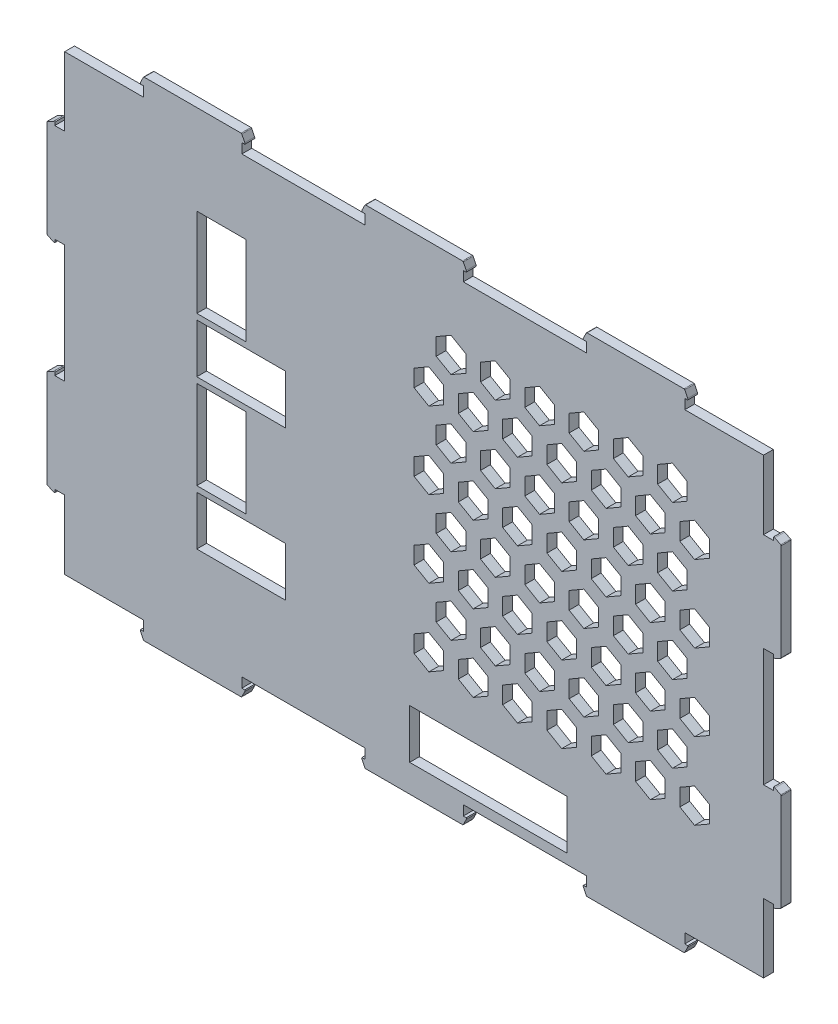
SolidWorks part; units mm, degrees
ref_plane "Front Plane" through (0, 0, 0) normal (0, 0, 1) x (1, 0, 0)
ref_plane "Top Plane" through (0, 0, 0) normal (0, 1, 0) x (1, 0, 0)
ref_plane "Right Plane" through (0, 0, 0) normal (1, 0, 0) x (0, 0, -1)
sketch "Sketch1" plane through (0, 0, 0) normal (0, 0, 1) x (1, 0, 0)
  line L0 (0, 0) -> (142, 0) construction
  line L1 (142, -46) -> (142, 46) construction
  line L2 (142, 46) -> (0, 46) construction
  line L3 (0, 46) -> (0, -46) construction
  line L8 (0, -46) -> (142, -46) construction
  line L30 (71, 46) -> (71, -46) construction
  line L31 (0, 32) -> (0, 46)
  line L32 (0, 46) -> (16, 46)
  line L35 (36, 46) -> (61, 46)
  line L37 (81, 46) -> (106, 46)
  line L39 (126, 46) -> (142, 46)
  line L40 (142, 46) -> (142, 32)
  line L43 (142, -46) -> (126, -46)
  line L46 (106, -46) -> (81, -46)
  line L48 (61, -46) -> (36, -46)
  line L50 (16, -46) -> (0, -46)
  line L51 (0, -46) -> (0, -32)
  line L52 (0, -12) -> (0, 12)
  line L54 (142, 12) -> (142, -12)
  line L56 (142, -32) -> (142, -46)
  line B0 (16, -46) -> (36, -46) construction
  line B1 (16.1618, -49.6) -> (35.8382, -49.6)
  line B2 (16, -46) -> (16, -48)
  line B3 (16, -49.5) -> (36, -49.5) construction
  line B4 (26, -49.5) -> (26, -46) construction
  line B5 (36, -46) -> (36, -48)
  line B6 (36.6, -48.3) -> (36, -49.5)
  line B7 (15.4, -48.3) -> (16, -49.5)
  line B8 (16, -48) -> (15.4, -48)
  line B9 (36, -48) -> (36.6, -48)
  arc B10 (16, -48) -> (15.4, -48.3) centre (15.7, -48.15) ccw construction
  arc B11 (16, -49.5) -> (16.1618, -49.6) centre (16.1618, -49.4191) ccw
  arc B12 (36, -49.5) -> (35.8382, -49.6) centre (35.8382, -49.4191) cw
  arc B13 (15.4, -48) -> (15.4, -48.3) centre (15.7, -48.15) ccw
  arc B14 (36.6, -48) -> (36.6, -48.3) centre (36.3, -48.15) cw
  line B15 (61, -46) -> (81, -46) construction
  line B16 (61.1618, -49.6) -> (80.8382, -49.6)
  line B17 (61, -46) -> (61, -48)
  line B18 (61, -49.5) -> (81, -49.5) construction
  line B19 (71, -49.5) -> (71, -46) construction
  line B20 (81, -46) -> (81, -48)
  line B21 (81.6, -48.3) -> (81, -49.5)
  line B22 (60.4, -48.3) -> (61, -49.5)
  line B23 (61, -48) -> (60.4, -48)
  line B24 (81, -48) -> (81.6, -48)
  arc B25 (61, -48) -> (60.4, -48.3) centre (60.7, -48.15) ccw construction
  arc B26 (61, -49.5) -> (61.1618, -49.6) centre (61.1618, -49.4191) ccw
  arc B27 (81, -49.5) -> (80.8382, -49.6) centre (80.8382, -49.4191) cw
  arc B28 (60.4, -48) -> (60.4, -48.3) centre (60.7, -48.15) ccw
  arc B29 (81.6, -48) -> (81.6, -48.3) centre (81.3, -48.15) cw
  line B30 (142, 12) -> (142, 32) construction
  line B31 (145.6, 12.1618) -> (145.6, 31.8382)
  line B32 (142, 12) -> (144, 12)
  line B33 (145.5, 12) -> (145.5, 32) construction
  line B34 (145.5, 22) -> (142, 22) construction
  line B35 (142, 32) -> (144, 32)
  line B36 (144.3, 32.6) -> (145.5, 32)
  line B37 (144.3, 11.4) -> (145.5, 12)
  line B38 (144, 12) -> (144, 11.4)
  line B39 (144, 32) -> (144, 32.6)
  arc B40 (144, 12) -> (144.3, 11.4) centre (144.15, 11.7) ccw construction
  arc B41 (145.5, 12) -> (145.6, 12.1618) centre (145.4191, 12.1618) ccw
  arc B42 (145.5, 32) -> (145.6, 31.8382) centre (145.4191, 31.8382) cw
  arc B43 (144, 11.4) -> (144.3, 11.4) centre (144.15, 11.7) ccw
  arc B44 (144, 32.6) -> (144.3, 32.6) centre (144.15, 32.3) cw
  line B45 (126, -46) -> (106, -46) construction
  line B46 (125.8382, -49.6) -> (106.1618, -49.6)
  line B47 (126, -46) -> (126, -48)
  line B48 (126, -49.5) -> (106, -49.5) construction
  line B49 (116, -49.5) -> (116, -46) construction
  line B50 (106, -46) -> (106, -48)
  line B51 (105.4, -48.3) -> (106, -49.5)
  line B52 (126.6, -48.3) -> (126, -49.5)
  line B53 (126, -48) -> (126.6, -48)
  line B54 (106, -48) -> (105.4, -48)
  arc B55 (126, -48) -> (126.6, -48.3) centre (126.3, -48.15) cw construction
  arc B56 (126, -49.5) -> (125.8382, -49.6) centre (125.8382, -49.4191) cw
  arc B57 (106, -49.5) -> (106.1618, -49.6) centre (106.1618, -49.4191) ccw
  arc B58 (126.6, -48) -> (126.6, -48.3) centre (126.3, -48.15) cw
  arc B59 (105.4, -48) -> (105.4, -48.3) centre (105.7, -48.15) ccw
  line B60 (16, 46) -> (36, 46) construction
  line B61 (16.1618, 49.6) -> (35.8382, 49.6)
  line B62 (16, 46) -> (16, 48)
  line B63 (16, 49.5) -> (36, 49.5) construction
  line B64 (26, 49.5) -> (26, 46) construction
  line B65 (36, 46) -> (36, 48)
  line B66 (36.6, 48.3) -> (36, 49.5)
  line B67 (15.4, 48.3) -> (16, 49.5)
  line B68 (16, 48) -> (15.4, 48)
  line B69 (36, 48) -> (36.6, 48)
  arc B70 (16, 48) -> (15.4, 48.3) centre (15.7, 48.15) cw construction
  arc B71 (16, 49.5) -> (16.1618, 49.6) centre (16.1618, 49.4191) cw
  arc B72 (36, 49.5) -> (35.8382, 49.6) centre (35.8382, 49.4191) ccw
  arc B73 (15.4, 48) -> (15.4, 48.3) centre (15.7, 48.15) cw
  arc B74 (36.6, 48) -> (36.6, 48.3) centre (36.3, 48.15) ccw
  line B75 (61, 46) -> (81, 46) construction
  line B76 (61.1618, 49.6) -> (80.8382, 49.6)
  line B77 (61, 46) -> (61, 48)
  line B78 (61, 49.5) -> (81, 49.5) construction
  line B79 (71, 49.5) -> (71, 46) construction
  line B80 (81, 46) -> (81, 48)
  line B81 (81.6, 48.3) -> (81, 49.5)
  line B82 (60.4, 48.3) -> (61, 49.5)
  line B83 (61, 48) -> (60.4, 48)
  line B84 (81, 48) -> (81.6, 48)
  arc B85 (61, 48) -> (60.4, 48.3) centre (60.7, 48.15) cw construction
  arc B86 (61, 49.5) -> (61.1618, 49.6) centre (61.1618, 49.4191) cw
  arc B87 (81, 49.5) -> (80.8382, 49.6) centre (80.8382, 49.4191) ccw
  arc B88 (60.4, 48) -> (60.4, 48.3) centre (60.7, 48.15) cw
  arc B89 (81.6, 48) -> (81.6, 48.3) centre (81.3, 48.15) ccw
  line B90 (126, 46) -> (106, 46) construction
  line B91 (125.8382, 49.6) -> (106.1618, 49.6)
  line B92 (126, 46) -> (126, 48)
  line B93 (126, 49.5) -> (106, 49.5) construction
  line B94 (116, 49.5) -> (116, 46) construction
  line B95 (106, 46) -> (106, 48)
  line B96 (105.4, 48.3) -> (106, 49.5)
  line B97 (126.6, 48.3) -> (126, 49.5)
  line B98 (126, 48) -> (126.6, 48)
  line B99 (106, 48) -> (105.4, 48)
  arc B100 (126, 48) -> (126.6, 48.3) centre (126.3, 48.15) ccw construction
  arc B101 (126, 49.5) -> (125.8382, 49.6) centre (125.8382, 49.4191) ccw
  arc B102 (106, 49.5) -> (106.1618, 49.6) centre (106.1618, 49.4191) cw
  arc B103 (126.6, 48) -> (126.6, 48.3) centre (126.3, 48.15) ccw
  arc B104 (105.4, 48) -> (105.4, 48.3) centre (105.7, 48.15) cw
  line B105 (0, 12) -> (0, 32) construction
  line B106 (-3.6, 12.1618) -> (-3.6, 31.8382)
  line B107 (0, 12) -> (-2, 12)
  line B108 (-3.5, 12) -> (-3.5, 32) construction
  line B109 (-3.5, 22) -> (0, 22) construction
  line B110 (0, 32) -> (-2, 32)
  line B111 (-2.3, 32.6) -> (-3.5, 32)
  line B112 (-2.3, 11.4) -> (-3.5, 12)
  line B113 (-2, 12) -> (-2, 11.4)
  line B114 (-2, 32) -> (-2, 32.6)
  arc B115 (-2, 12) -> (-2.3, 11.4) centre (-2.15, 11.7) cw construction
  arc B116 (-3.5, 12) -> (-3.6, 12.1618) centre (-3.4191, 12.1618) cw
  arc B117 (-3.5, 32) -> (-3.6, 31.8382) centre (-3.4191, 31.8382) ccw
  arc B118 (-2, 11.4) -> (-2.3, 11.4) centre (-2.15, 11.7) cw
  arc B119 (-2, 32.6) -> (-2.3, 32.6) centre (-2.15, 32.3) ccw
  line B120 (26.8458, 12.2196) -> (44.8458, 12.2196)
  line B121 (26.8458, 12.2196) -> (26.8458, 2.2196)
  line B122 (26.8458, 2.2196) -> (44.8458, 2.2196)
  line B123 (44.8458, 12.2196) -> (44.8458, 2.2196)
  line B124 (26.8458, -18.0919) -> (44.8458, -18.0919)
  line B125 (26.8458, -18.0919) -> (26.8458, -28.0919)
  line B126 (26.8458, -28.0919) -> (44.8458, -28.0919)
  line B127 (44.8458, -18.0919) -> (44.8458, -28.0919)
  line B128 (36.8458, 1.0639) -> (36.8458, -16.9361)
  line B129 (36.8458, 1.0639) -> (26.8458, 1.0639)
  line B130 (26.8458, 1.0639) -> (26.8458, -16.9361)
  line B131 (36.8458, -16.9361) -> (26.8458, -16.9361)
  line B132 (36.8458, 31.3754) -> (36.8458, 13.3754)
  line B133 (36.8458, 31.3754) -> (26.8458, 31.3754)
  line B134 (26.8458, 31.3754) -> (26.8458, 13.3754)
  line B135 (36.8458, 13.3754) -> (26.8458, 13.3754)
  line B136 (26.8458, 13.3754) -> (26.8458, 12.2196) construction
  line B137 (26.8458, 2.2196) -> (26.8458, 1.0639) construction
  line B138 (26.8458, -16.9361) -> (26.8458, -18.0919) construction
  line B139 (70.1, -34) -> (102.1, -34)
  line B140 (70.1, -34) -> (70.1, -44)
  line B141 (70.1, -44) -> (102.1, -44)
  line B142 (102.1, -34) -> (102.1, -44)
  line B143 (0, 46) -> (142, 46) construction
  line B144 (142, 46) -> (142, -46) construction
  line B145 (142, -46) -> (0, -46) construction
  line B146 (0, -46) -> (0, 46) construction
  line B147 (142, -12) -> (142, -32) construction
  line B148 (145.6, -12.1618) -> (145.6, -31.8382)
  line B149 (142, -12) -> (144, -12)
  line B150 (145.5, -12) -> (145.5, -32) construction
  line B151 (145.5, -22) -> (142, -22) construction
  line B152 (142, -32) -> (144, -32)
  line B153 (144.3, -32.6) -> (145.5, -32)
  line B154 (144.3, -11.4) -> (145.5, -12)
  line B155 (144, -12) -> (144, -11.4)
  line B156 (144, -32) -> (144, -32.6)
  arc B157 (144, -12) -> (144.3, -11.4) centre (144.15, -11.7) cw construction
  arc B158 (145.5, -12) -> (145.6, -12.1618) centre (145.4191, -12.1618) cw
  arc B159 (145.5, -32) -> (145.6, -31.8382) centre (145.4191, -31.8382) ccw
  arc B160 (144, -11.4) -> (144.3, -11.4) centre (144.15, -11.7) cw
  arc B161 (144, -32.6) -> (144.3, -32.6) centre (144.15, -32.3) ccw
  line B162 (0, -12) -> (0, -32) construction
  line B163 (-3.6, -12.1618) -> (-3.6, -31.8382)
  line B164 (0, -12) -> (-2, -12)
  line B165 (-3.5, -12) -> (-3.5, -32) construction
  line B166 (-3.5, -22) -> (0, -22) construction
  line B167 (0, -32) -> (-2, -32)
  line B168 (-2.3, -32.6) -> (-3.5, -32)
  line B169 (-2.3, -11.4) -> (-3.5, -12)
  line B170 (-2, -12) -> (-2, -11.4)
  line B171 (-2, -32) -> (-2, -32.6)
  arc B172 (-2, -12) -> (-2.3, -11.4) centre (-2.15, -11.7) ccw construction
  arc B173 (-3.5, -12) -> (-3.6, -12.1618) centre (-3.4191, -12.1618) ccw
  arc B174 (-3.5, -32) -> (-3.6, -31.8382) centre (-3.4191, -31.8382) cw
  arc B175 (-2, -11.4) -> (-2.3, -11.4) centre (-2.15, -11.7) ccw
  arc B176 (-2, -32.6) -> (-2.3, -32.6) centre (-2.15, -32.3) cw
  dimension "D2" = 22
  dimension "D3" = 45
  dimension "D1" = 142
sketch_block_instance "insert_bloquant_20mm-2mm-1"
sketch_block "insert_bloquant_20mm-2mm" parameters "D1"=2, "D2"=1.5, "D3"=1.2, "D4"=20, "D5"=0.1, "D6"=0.6
sketch_block_instance "insert_bloquant_20mm-2mm-2"
sketch_block_instance "insert_bloquant_20mm-2mm-4"
sketch_block_instance "insert_bloquant_20mm-2mm-6"
sketch_block_instance "insert_bloquant_20mm-2mm-7"
sketch_block_instance "insert_bloquant_20mm-2mm-8"
sketch_block_instance "insert_bloquant_20mm-2mm-9"
sketch_block_instance "insert_bloquant_20mm-2mm-13"
sketch_block_instance "Bloc1-1"
sketch_block "Bloc1" parameters "D1"=10, "D2"=32
sketch_block_instance "Block1-1"
sketch_block "Block1" parameters "D1"=18, "D2"=10
sketch_block_instance "Block1-2"
sketch_block_instance "Block1-3"
sketch_block_instance "Block1-4"
sketch_block_instance "insert_bloquant_20mm-2mm-14"
sketch_block_instance "insert_bloquant_20mm-2mm-15"
extrude "Boss-Extrude1" add sketch "Sketch1" along normal blind 2
sketch "Esquisse1" plane through (0, 0, 2) normal (0, 0, 1) x (1, 0, 0)
  line L5 (71, 49.6) -> (71, -49.6) construction
  line L6 (61.1618, 49.6) -> (80.8382, 49.6) construction
  line L7 (61.1618, -49.6) -> (80.8382, -49.6) construction
  line B0 (131, 10.236) -> (128, 11.968)
  line B1 (128, 11.968) -> (125, 10.236)
  line B2 (120.5, 14.5661) -> (123.5, 12.834)
  line B3 (126.5, 14.5661) -> (126.5, 18.0302)
  line B4 (126.5, 18.0302) -> (123.5, 19.7622)
  line B5 (123.5, 19.7622) -> (120.5, 18.0302)
  line B6 (122, 6.7719) -> (122, 10.236)
  line B7 (122, 10.236) -> (119, 11.968)
  line B8 (119, 11.968) -> (116, 10.236)
  line B9 (111.5, 14.5661) -> (114.5, 12.834)
  line B10 (117.5, 14.5661) -> (117.5, 18.0302)
  line B11 (117.5, 18.0302) -> (114.5, 19.7622)
  line B12 (114.5, 19.7622) -> (111.5, 18.0302)
  line B13 (107, 6.7719) -> (110, 5.0398)
  line B14 (113, 6.7719) -> (113, 10.236)
  line B15 (113, 10.236) -> (110, 11.968)
  line B16 (110, 11.968) -> (107, 10.236)
  line B17 (102.5, 14.5661) -> (105.5, 12.834)
  line B18 (108.5, 14.5661) -> (108.5, 18.0302)
  line B19 (108.5, 18.0302) -> (105.5, 19.7622)
  line B20 (105.5, 19.7622) -> (102.5, 18.0302)
  line B21 (98, 6.7719) -> (101, 5.0398)
  line B22 (95, 6.7719) -> (95, 10.236)
  line B23 (128, 5.0398) -> (131, 6.7719)
  line B24 (104, 6.7719) -> (104, 10.236)
  line B25 (104, 10.236) -> (101, 11.968)
  line B26 (101, 11.968) -> (98, 10.236)
  line B27 (95, 10.236) -> (92, 11.968)
  line B28 (92, 11.968) -> (89, 10.236)
  line B29 (84.5, 14.5661) -> (87.5, 12.834)
  line B30 (90.5, 14.5661) -> (90.5, 18.0302)
  line B31 (90.5, 18.0302) -> (87.5, 19.7622)
  line B32 (87.5, 19.7622) -> (84.5, 18.0302)
  line B33 (80, 6.7719) -> (83, 5.0398)
  line B34 (86, 6.7719) -> (86, 10.236)
  line B35 (86, 10.236) -> (83, 11.968)
  line B36 (83, 11.968) -> (80, 10.236)
  line B37 (75.5, 14.5661) -> (78.5, 12.834)
  line B38 (81.5, 14.5661) -> (81.5, 18.0302)
  line B39 (81.5, 18.0302) -> (78.5, 19.7622)
  line B40 (78.5, 19.7622) -> (75.5, 18.0302)
  line B41 (71, 6.7719) -> (74, 5.0398)
  line B42 (77, 6.7719) -> (77, 10.236)
  line B43 (77, 10.236) -> (74, 11.968)
  line B44 (74, 11.968) -> (71, 10.236)
  line B45 (99.5, 18.0302) -> (96.5, 19.7622)
  line B46 (96.5, 19.7622) -> (93.5, 18.0302)
  line B47 (125, 6.7719) -> (128, 5.0398)
  line B48 (131, 6.7719) -> (131, 10.236)
  line B49 (125, 10.236) -> (125, 6.7719)
  line B50 (123.5, 12.834) -> (126.5, 14.5661)
  line B51 (120.5, 18.0302) -> (120.5, 14.5661)
  line B52 (80, 10.236) -> (80, 6.7719)
  line B53 (83, 5.0398) -> (86, 6.7719)
  line B54 (98, 10.236) -> (98, 6.7719)
  line B55 (101, 5.0398) -> (104, 6.7719)
  line B56 (116, 10.236) -> (116, 6.7719)
  line B57 (116, 6.7719) -> (119, 5.0398)
  line B58 (119, 5.0398) -> (122, 6.7719)
  line B59 (111.5, 18.0302) -> (111.5, 14.5661)
  line B60 (114.5, 12.834) -> (117.5, 14.5661)
  line B61 (74, 5.0398) -> (77, 6.7719)
  line B62 (71, 10.236) -> (71, 6.7719)
  line B63 (78.5, 12.834) -> (81.5, 14.5661)
  line B64 (75.5, 18.0302) -> (75.5, 14.5661)
  line B65 (92, 5.0398) -> (95, 6.7719)
  line B66 (89, 6.7719) -> (92, 5.0398)
  line B67 (89, 10.236) -> (89, 6.7719)
  line B68 (87.5, 12.834) -> (90.5, 14.5661)
  line B69 (84.5, 18.0302) -> (84.5, 14.5661)
  line B70 (96.5, 12.834) -> (99.5, 14.5661)
  line B71 (93.5, 14.5661) -> (96.5, 12.834)
  line B72 (93.5, 18.0302) -> (93.5, 14.5661)
  line B73 (99.5, 14.5661) -> (99.5, 18.0302)
  line B74 (110, 5.0398) -> (113, 6.7719)
  line B75 (107, 10.236) -> (107, 6.7719)
  line B76 (105.5, 12.834) -> (108.5, 14.5661)
  line B77 (102.5, 18.0302) -> (102.5, 14.5661)
  line B78 (131, 25.8244) -> (128, 27.5565)
  line B79 (128, 27.5565) -> (125, 25.8244)
  line B80 (120.5, 30.1546) -> (123.5, 28.4225)
  line B81 (126.5, 30.1546) -> (126.5, 33.6187)
  line B82 (126.5, 33.6187) -> (123.5, 35.3507)
  line B83 (123.5, 35.3507) -> (120.5, 33.6187)
  line B84 (122, 22.3603) -> (122, 25.8244)
  line B85 (122, 25.8244) -> (119, 27.5565)
  line B86 (119, 27.5565) -> (116, 25.8244)
  line B87 (111.5, 30.1546) -> (114.5, 28.4225)
  line B88 (117.5, 30.1546) -> (117.5, 33.6187)
  line B89 (117.5, 33.6187) -> (114.5, 35.3507)
  line B90 (114.5, 35.3507) -> (111.5, 33.6187)
  line B91 (107, 22.3603) -> (110, 20.6283)
  line B92 (113, 22.3603) -> (113, 25.8244)
  line B93 (113, 25.8244) -> (110, 27.5565)
  line B94 (110, 27.5565) -> (107, 25.8244)
  line B95 (102.5, 30.1546) -> (105.5, 28.4225)
  line B96 (108.5, 30.1546) -> (108.5, 33.6187)
  line B97 (108.5, 33.6187) -> (105.5, 35.3507)
  line B98 (105.5, 35.3507) -> (102.5, 33.6187)
  line B99 (98, 22.3603) -> (101, 20.6283)
  line B100 (95, 22.3603) -> (95, 25.8244)
  line B101 (128, 20.6283) -> (131, 22.3603)
  line B102 (104, 22.3603) -> (104, 25.8244)
  line B103 (104, 25.8244) -> (101, 27.5565)
  line B104 (101, 27.5565) -> (98, 25.8244)
  line B105 (95, 25.8244) -> (92, 27.5565)
  line B106 (92, 27.5565) -> (89, 25.8244)
  line B107 (84.5, 30.1546) -> (87.5, 28.4225)
  line B108 (90.5, 30.1546) -> (90.5, 33.6187)
  line B109 (90.5, 33.6187) -> (87.5, 35.3507)
  line B110 (87.5, 35.3507) -> (84.5, 33.6187)
  line B111 (80, 22.3603) -> (83, 20.6283)
  line B112 (86, 22.3603) -> (86, 25.8244)
  line B113 (86, 25.8244) -> (83, 27.5565)
  line B114 (83, 27.5565) -> (80, 25.8244)
  line B115 (75.5, 30.1546) -> (78.5, 28.4225)
  line B116 (81.5, 30.1546) -> (81.5, 33.6187)
  line B117 (81.5, 33.6187) -> (78.5, 35.3507)
  line B118 (78.5, 35.3507) -> (75.5, 33.6187)
  line B119 (71, 22.3603) -> (74, 20.6283)
  line B120 (77, 22.3603) -> (77, 25.8244)
  line B121 (77, 25.8244) -> (74, 27.5565)
  line B122 (74, 27.5565) -> (71, 25.8244)
  line B123 (99.5, 33.6187) -> (96.5, 35.3507)
  line B124 (96.5, 35.3507) -> (93.5, 33.6187)
  line B125 (125, 22.3603) -> (128, 20.6283)
  line B126 (131, 22.3603) -> (131, 25.8244)
  line B127 (125, 25.8244) -> (125, 22.3603)
  line B128 (123.5, 28.4225) -> (126.5, 30.1546)
  line B129 (120.5, 33.6187) -> (120.5, 30.1546)
  line B130 (80, 25.8244) -> (80, 22.3603)
  line B131 (83, 20.6283) -> (86, 22.3603)
  line B132 (98, 25.8244) -> (98, 22.3603)
  line B133 (101, 20.6283) -> (104, 22.3603)
  line B134 (116, 25.8244) -> (116, 22.3603)
  line B135 (116, 22.3603) -> (119, 20.6283)
  line B136 (119, 20.6283) -> (122, 22.3603)
  line B137 (111.5, 33.6187) -> (111.5, 30.1546)
  line B138 (114.5, 28.4225) -> (117.5, 30.1546)
  line B139 (74, 20.6283) -> (77, 22.3603)
  line B140 (71, 25.8244) -> (71, 22.3603)
  line B141 (78.5, 28.4225) -> (81.5, 30.1546)
  line B142 (75.5, 33.6187) -> (75.5, 30.1546)
  line B143 (92, 20.6283) -> (95, 22.3603)
  line B144 (89, 22.3603) -> (92, 20.6283)
  line B145 (89, 25.8244) -> (89, 22.3603)
  line B146 (87.5, 28.4225) -> (90.5, 30.1546)
  line B147 (84.5, 33.6187) -> (84.5, 30.1546)
  line B148 (96.5, 28.4225) -> (99.5, 30.1546)
  line B149 (93.5, 30.1546) -> (96.5, 28.4225)
  line B150 (93.5, 33.6187) -> (93.5, 30.1546)
  line B151 (99.5, 30.1546) -> (99.5, 33.6187)
  line B152 (110, 20.6283) -> (113, 22.3603)
  line B153 (107, 25.8244) -> (107, 22.3603)
  line B154 (105.5, 28.4225) -> (108.5, 30.1546)
  line B155 (102.5, 33.6187) -> (102.5, 30.1546)
  line B156 (131, -20.9409) -> (128, -19.2089)
  line B157 (128, -19.2089) -> (125, -20.9409)
  line B158 (120.5, -16.6108) -> (123.5, -18.3429)
  line B159 (126.5, -16.6108) -> (126.5, -13.1467)
  line B160 (126.5, -13.1467) -> (123.5, -11.4147)
  line B161 (123.5, -11.4147) -> (120.5, -13.1467)
  line B162 (122, -24.4051) -> (122, -20.9409)
  line B163 (122, -20.9409) -> (119, -19.2089)
  line B164 (119, -19.2089) -> (116, -20.9409)
  line B165 (111.5, -16.6108) -> (114.5, -18.3429)
  line B166 (117.5, -16.6108) -> (117.5, -13.1467)
  line B167 (117.5, -13.1467) -> (114.5, -11.4147)
  line B168 (114.5, -11.4147) -> (111.5, -13.1467)
  line B169 (107, -24.4051) -> (110, -26.1371)
  line B170 (113, -24.4051) -> (113, -20.9409)
  line B171 (113, -20.9409) -> (110, -19.2089)
  line B172 (110, -19.2089) -> (107, -20.9409)
  line B173 (102.5, -16.6108) -> (105.5, -18.3429)
  line B174 (108.5, -16.6108) -> (108.5, -13.1467)
  line B175 (108.5, -13.1467) -> (105.5, -11.4147)
  line B176 (105.5, -11.4147) -> (102.5, -13.1467)
  line B177 (98, -24.4051) -> (101, -26.1371)
  line B178 (95, -24.4051) -> (95, -20.9409)
  line B179 (128, -26.1371) -> (131, -24.4051)
  line B180 (104, -24.4051) -> (104, -20.9409)
  line B181 (104, -20.9409) -> (101, -19.2089)
  line B182 (101, -19.2089) -> (98, -20.9409)
  line B183 (95, -20.9409) -> (92, -19.2089)
  line B184 (92, -19.2089) -> (89, -20.9409)
  line B185 (84.5, -16.6108) -> (87.5, -18.3429)
  line B186 (90.5, -16.6108) -> (90.5, -13.1467)
  line B187 (90.5, -13.1467) -> (87.5, -11.4147)
  line B188 (87.5, -11.4147) -> (84.5, -13.1467)
  line B189 (80, -24.4051) -> (83, -26.1371)
  line B190 (86, -24.4051) -> (86, -20.9409)
  line B191 (86, -20.9409) -> (83, -19.2089)
  line B192 (83, -19.2089) -> (80, -20.9409)
  line B193 (75.5, -16.6108) -> (78.5, -18.3429)
  line B194 (81.5, -16.6108) -> (81.5, -13.1467)
  line B195 (81.5, -13.1467) -> (78.5, -11.4147)
  line B196 (78.5, -11.4147) -> (75.5, -13.1467)
  line B197 (71, -24.4051) -> (74, -26.1371)
  line B198 (77, -24.4051) -> (77, -20.9409)
  line B199 (77, -20.9409) -> (74, -19.2089)
  line B200 (74, -19.2089) -> (71, -20.9409)
  line B201 (99.5, -13.1467) -> (96.5, -11.4147)
  line B202 (96.5, -11.4147) -> (93.5, -13.1467)
  line B203 (125, -24.4051) -> (128, -26.1371)
  line B204 (131, -24.4051) -> (131, -20.9409)
  line B205 (125, -20.9409) -> (125, -24.4051)
  line B206 (123.5, -18.3429) -> (126.5, -16.6108)
  line B207 (120.5, -13.1467) -> (120.5, -16.6108)
  line B208 (80, -20.9409) -> (80, -24.4051)
  line B209 (83, -26.1371) -> (86, -24.4051)
  line B210 (98, -20.9409) -> (98, -24.4051)
  line B211 (101, -26.1371) -> (104, -24.4051)
  line B212 (128, -22.673) -> (71, -22.673) construction
  line B213 (116, -20.9409) -> (116, -24.4051)
  line B214 (116, -24.4051) -> (119, -26.1371)
  line B215 (119, -26.1371) -> (122, -24.4051)
  line B216 (111.5, -13.1467) -> (111.5, -16.6108)
  line B217 (114.5, -18.3429) -> (117.5, -16.6108)
  line B218 (74, -26.1371) -> (77, -24.4051)
  line B219 (71, -20.9409) -> (71, -24.4051)
  line B220 (78.5, -18.3429) -> (81.5, -16.6108)
  line B221 (75.5, -13.1467) -> (75.5, -16.6108)
  line B222 (92, -26.1371) -> (95, -24.4051)
  line B223 (89, -24.4051) -> (92, -26.1371)
  line B224 (89, -20.9409) -> (89, -24.4051)
  line B225 (87.5, -18.3429) -> (90.5, -16.6108)
  line B226 (84.5, -13.1467) -> (84.5, -16.6108)
  line B227 (96.5, -18.3429) -> (99.5, -16.6108)
  line B228 (93.5, -16.6108) -> (96.5, -18.3429)
  line B229 (93.5, -13.1467) -> (93.5, -16.6108)
  line B230 (99.5, -16.6108) -> (99.5, -13.1467)
  line B231 (110, -26.1371) -> (113, -24.4051)
  line B232 (107, -20.9409) -> (107, -24.4051)
  line B233 (105.5, -18.3429) -> (108.5, -16.6108)
  line B234 (102.5, -13.1467) -> (102.5, -16.6108)
  line B235 (131, -5.3525) -> (128, -3.6204)
  line B236 (128, -3.6204) -> (125, -5.3525)
  line B237 (120.5, -1.0224) -> (123.5, -2.7544)
  line B238 (126.5, -1.0224) -> (126.5, 2.4417)
  line B239 (126.5, 2.4417) -> (123.5, 4.1738)
  line B240 (123.5, 4.1738) -> (120.5, 2.4417)
  line B241 (122, -8.8166) -> (122, -5.3525)
  line B242 (122, -5.3525) -> (119, -3.6204)
  line B243 (119, -3.6204) -> (116, -5.3525)
  line B244 (111.5, -1.0224) -> (114.5, -2.7544)
  line B245 (117.5, -1.0224) -> (117.5, 2.4417)
  line B246 (117.5, 2.4417) -> (114.5, 4.1738)
  line B247 (114.5, 4.1738) -> (111.5, 2.4417)
  line B248 (107, -8.8166) -> (110, -10.5486)
  line B249 (113, -8.8166) -> (113, -5.3525)
  line B250 (113, -5.3525) -> (110, -3.6204)
  line B251 (110, -3.6204) -> (107, -5.3525)
  line B252 (102.5, -1.0224) -> (105.5, -2.7544)
  line B253 (108.5, -1.0224) -> (108.5, 2.4417)
  line B254 (108.5, 2.4417) -> (105.5, 4.1738)
  line B255 (105.5, 4.1738) -> (102.5, 2.4417)
  line B256 (98, -8.8166) -> (101, -10.5486)
  line B257 (95, -8.8166) -> (95, -5.3525)
  line B258 (128, -10.5486) -> (131, -8.8166)
  line B259 (104, -8.8166) -> (104, -5.3525)
  line B260 (104, -5.3525) -> (101, -3.6204)
  line B261 (101, -3.6204) -> (98, -5.3525)
  line B262 (95, -5.3525) -> (92, -3.6204)
  line B263 (92, -3.6204) -> (89, -5.3525)
  line B264 (84.5, -1.0224) -> (87.5, -2.7544)
  line B265 (90.5, -1.0224) -> (90.5, 2.4417)
  line B266 (90.5, 2.4417) -> (87.5, 4.1738)
  line B267 (87.5, 4.1738) -> (84.5, 2.4417)
  line B268 (80, -8.8166) -> (83, -10.5486)
  line B269 (86, -8.8166) -> (86, -5.3525)
  line B270 (86, -5.3525) -> (83, -3.6204)
  line B271 (83, -3.6204) -> (80, -5.3525)
  line B272 (75.5, -1.0224) -> (78.5, -2.7544)
  line B273 (81.5, -1.0224) -> (81.5, 2.4417)
  line B274 (81.5, 2.4417) -> (78.5, 4.1738)
  line B275 (78.5, 4.1738) -> (75.5, 2.4417)
  line B276 (71, -8.8166) -> (74, -10.5486)
  line B277 (77, -8.8166) -> (77, -5.3525)
  line B278 (77, -5.3525) -> (74, -3.6204)
  line B279 (74, -3.6204) -> (71, -5.3525)
  line B280 (99.5, 2.4417) -> (96.5, 4.1738)
  line B281 (96.5, 4.1738) -> (93.5, 2.4417)
  line B282 (125, -8.8166) -> (128, -10.5486)
  line B283 (131, -8.8166) -> (131, -5.3525)
  line B284 (125, -5.3525) -> (125, -8.8166)
  line B285 (123.5, -2.7544) -> (126.5, -1.0224)
  line B286 (120.5, 2.4417) -> (120.5, -1.0224)
  line B287 (80, -5.3525) -> (80, -8.8166)
  line B288 (83, -10.5486) -> (86, -8.8166)
  line B289 (98, -5.3525) -> (98, -8.8166)
  line B290 (101, -10.5486) -> (104, -8.8166)
  line B291 (128, -7.0845) -> (71, -7.0845) construction
  line B292 (116, -5.3525) -> (116, -8.8166)
  line B293 (116, -8.8166) -> (119, -10.5486)
  line B294 (119, -10.5486) -> (122, -8.8166)
  line B295 (111.5, 2.4417) -> (111.5, -1.0224)
  line B296 (114.5, -2.7544) -> (117.5, -1.0224)
  line B297 (74, -10.5486) -> (77, -8.8166)
  line B298 (71, -5.3525) -> (71, -8.8166)
  line B299 (78.5, -2.7544) -> (81.5, -1.0224)
  line B300 (75.5, 2.4417) -> (75.5, -1.0224)
  line B301 (92, -10.5486) -> (95, -8.8166)
  line B302 (89, -8.8166) -> (92, -10.5486)
  line B303 (89, -5.3525) -> (89, -8.8166)
  line B304 (87.5, -2.7544) -> (90.5, -1.0224)
  line B305 (84.5, 2.4417) -> (84.5, -1.0224)
  line B306 (96.5, -2.7544) -> (99.5, -1.0224)
  line B307 (93.5, -1.0224) -> (96.5, -2.7544)
  line B308 (93.5, 2.4417) -> (93.5, -1.0224)
  line B309 (99.5, -1.0224) -> (99.5, 2.4417)
  line B310 (110, -10.5486) -> (113, -8.8166)
  line B311 (107, -5.3525) -> (107, -8.8166)
  line B312 (105.5, -2.7544) -> (108.5, -1.0224)
  line B313 (102.5, 2.4417) -> (102.5, -1.0224)
sketch_block_instance "Alveole_9mm_3mm_8x2-4"
sketch_block "Alveole_9mm_3mm_8x2" parameters "D1"=7, "D2"=1.5, "D3"=13.2857, "D4"=14
sketch_block_instance "Alveole_9mm_3mm_8x2-5"
sketch_block_instance "Alveole_9mm_3mm_8x2-10"
sketch_block_instance "Alveole_9mm_3mm_8x2-11"
extrude "Enlèv. mat.-Extru.1" cut sketch "Esquisse1" against normal through all
